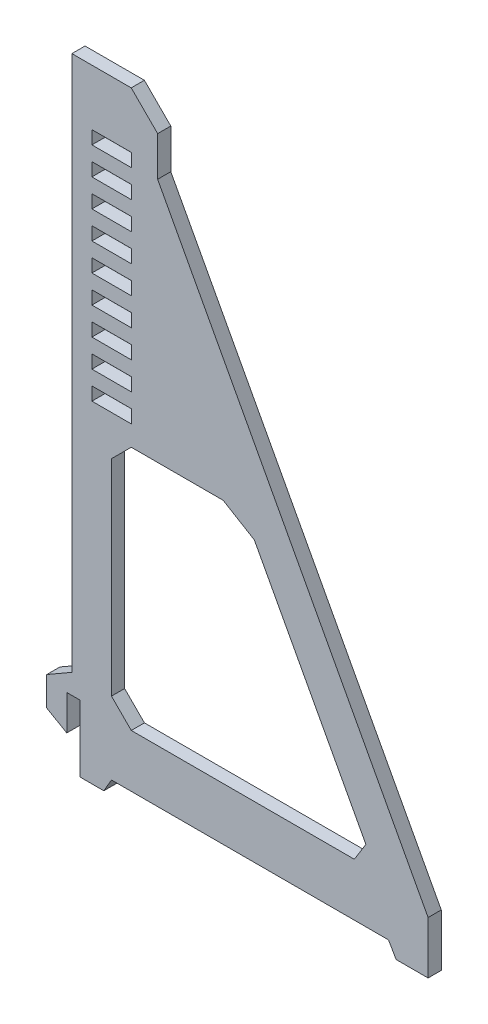
SolidWorks part; units mm, degrees
other "Markup1"
sketch "Sketch2" plane through (451.8627, 651.329, 334.843) normal (0.8622, 0.3297, 0.3847) x (0.4395, -0.109, -0.8916)
ref_plane "Front Plane" through (0, 0, 0) normal (0, 0, 1) x (1, 0, 0)
ref_plane "Top Plane" through (0, 0, 0) normal (0, 1, 0) x (1, 0, 0)
ref_plane "Right Plane" through (0, 0, 0) normal (1, 0, 0) x (0, 0, -1)
sketch "Sketch1" plane through (0, 0, 0) normal (0, 0, 1) x (1, 0, 0)
  line L1 (-15.6173, -25) -> (-13.1946, -25)
  line L2 (-15.6173, -25) -> (-15.6173, -22.8331)
  line L5 (-9.1173, 22.18) -> (-9.1173, 17.18)
  line L8 (-15.6173, 22.18) -> (-9.1173, 22.18)
  line L10 (-12.6173, -20) -> (7.4257, -20)
  line L11 (11.3827, -25) -> (11.3827, -21.0298)
  line L12 (-9.1173, 17.18) -> (11.3827, -21.0298)
  line L13 (-12.6173, -24) -> (8.3827, -24)
  line L14 (8.3827, -24) -> (8.9601, -25)
  line L15 (8.9601, -25) -> (9.8055, -25)
  line L16 (-12.6173, -1.41) -> (-2.548, -1.41) construction
  line L17 (-12.6173, -24) -> (-13.1946, -25)
  line L18 (8.9601, -25) -> (11.3827, -25)
  line L19 (-12.6173, -1.41) -> (-12.6173, -20)
  line L20 (-2.548, -1.41) -> (7.4257, -20)
  line L21 (-12.6173, -1.41) -> (-2.548, -1.41)
  line L22 (0.8565, -1.41) -> (27.1209, -1.41) construction
  line L23 (-15.6173, -18.4337) -> (-15.6173, 22.18)
  line L32 (-15.6173, -18.4337) -> (-17.5223, -19.5336)
  line L34 (-17.5223, -19.5336) -> (-17.5223, -21.7333)
  line L41 (-17.5223, -21.7333) -> (-15.6173, -22.8331)
  line L48 (-13.7123, -21.7333) -> (-13.7123, -19.5336) [skipped]
  line L49 (-14.6648, -18.9836) -> (-15.6173, -18.4337) [skipped]
  line L50 (-15.6173, -22.8331) -> (-14.6648, -22.2832) [skipped]
  point P0 (0, 0)
  dimension "D1" = 1
  dimension "D2" = 6.5
  dimension "D3" = 47.18
  dimension "D4" = 5
  dimension "D5" = 5
  dimension "D6" = 27
  dimension "D7" = 3
  dimension "D8" = 60
  dimension "D9" = 3
  dimension "D10" = 60
  dimension "D11" = 23.59
extrude "Boss-Extrude1" add sketch "Sketch1" along normal blind 25.4 contours L15 L18 L11 L12 L5 L8 L2 L1 L17 L13 L14 L19 L21 L20 L10
scale "Scale1" bodies to scale 101 scale about centroid uniform scaling yes scale factor 25.365591
sketch "Sketch3" plane through (0, 0, -309.443) normal (0, 0, -1) x (-1, 0, 0)
  line L1 (407.5134, -599.7995) -> (-634.8562, -599.7995)
  line L2 (407.5134, -599.7995) -> (407.5134, 673.4533)
  line L3 (407.5134, 673.4533) -> (-634.8562, 673.4533)
  line L4 (-634.8562, -599.7995) -> (-634.8562, 673.4533)
extrude "Cut-Extrude1" cut sketch "Sketch3" against normal blind 618.998
chamfer "Chamfer1" distance 50.8 angle 45 1 edges at (-65.0441, 656.7001, 322.199)
chamfer "Chamfer2" distance 38.1 angle 45 2 edges at (-153.8237, -413.2205, 322.199) (-153.8237, 58.3258, 322.199)
chamfer "Chamfer3" distance 40.64 angle 31 1 edges at (101.5889, 58.3258, 322.199)
chamfer "Chamfer4" distance 40.64 angle 60 1 edges at (354.5791, -413.2205, 322.199)
sketch "Sketch4" plane through (0, 0, 334.843) normal (0, 0, 1) x (1, 0, 0)
  line L0 (-229.9204, -540.0485) -> (-168.4685, -540.0485) construction
  line L1 (-214.3773, -540.0485) -> (-239.7773, -540.0485)
  line L2 (-214.3773, -540.0485) -> (-214.3773, -433.1771)
  line L3 (-214.3773, -433.1771) -> (-239.7773, -433.1771)
  line L4 (-239.7773, -540.0485) -> (-239.7773, -433.1771)
  dimension "D1" = 25.4
extrude "Cut-Extrude2" cut sketch "Sketch4" against normal blind 618.998 contours L2 L1 L4 L3
sketch "Sketch5" plane through (0, 0, 334.843) normal (0, 0, 1) x (1, 0, 0)
  line L0 (-191.4229, -540.0485) -> (-191.4229, 97.2375)
  line L1 (-214.3773, -540.0485) -> (-168.4685, -540.0485) construction
  line L2 (-191.4229, 150.5775) -> (-191.4229, 175.9775)
  line L3 (-191.4229, 97.2375) -> (-115.2229, 97.2375)
  line L4 (-191.4229, 97.2375) -> (-191.4229, 122.6375)
  line L5 (-191.4229, 122.6375) -> (-115.2229, 122.6375)
  line L6 (-115.2229, 97.2375) -> (-115.2229, 122.6375)
  line L7 (-191.4229, 150.5775) -> (-115.2229, 150.5775)
  line L8 (-115.2229, 150.5775) -> (-115.2229, 175.9775)
  line L9 (-191.4229, 175.9775) -> (-115.2229, 175.9775)
  line L10 (-191.4229, 203.9175) -> (-191.4229, 229.3175)
  line L11 (-191.4229, 203.9175) -> (-115.2229, 203.9175)
  line L12 (-115.2229, 203.9175) -> (-115.2229, 229.3175)
  line L13 (-191.4229, 229.3175) -> (-115.2229, 229.3175)
  line L14 (-191.4229, 257.2575) -> (-191.4229, 282.6575)
  line L15 (-191.4229, 257.2575) -> (-115.2229, 257.2575)
  line L16 (-115.2229, 257.2575) -> (-115.2229, 282.6575)
  line L17 (-191.4229, 282.6575) -> (-115.2229, 282.6575)
  line L18 (-191.4229, 310.5975) -> (-191.4229, 335.9975)
  line L19 (-191.4229, 310.5975) -> (-115.2229, 310.5975)
  line L20 (-115.2229, 310.5975) -> (-115.2229, 335.9975)
  line L21 (-191.4229, 335.9975) -> (-115.2229, 335.9975)
  line L22 (-191.4229, 363.9375) -> (-191.4229, 389.3375)
  line L23 (-191.4229, 363.9375) -> (-115.2229, 363.9375)
  line L24 (-115.2229, 363.9375) -> (-115.2229, 389.3375)
  line L25 (-191.4229, 389.3375) -> (-115.2229, 389.3375)
  line L26 (-191.4229, 417.2775) -> (-191.4229, 442.6775)
  line L27 (-191.4229, 417.2775) -> (-115.2229, 417.2775)
  line L28 (-115.2229, 417.2775) -> (-115.2229, 442.6775)
  line L29 (-191.4229, 442.6775) -> (-115.2229, 442.6775)
  line L30 (-201.6214, 424.1602) -> (-201.6214, 449.5602)
  line L31 (-201.6214, 424.1602) -> (-125.4214, 424.1602)
  line L32 (-125.4214, 424.1602) -> (-125.4214, 449.5602)
  line L33 (-201.6214, 449.5602) -> (-125.4214, 449.5602)
  dimension "D1" = 637.286
  dimension "D2" = 76.2
  dimension "D3" = 25.4
  dimension "D5" = 25.4
  dimension "D4" = 7
extrude "Cut-Extrude3" cut sketch "Sketch5" against normal through all contours L21 L18 L19 L20 | L13 L10 L11 L12 | L29 L28 L27 L26 | L25 L24 L23 L22 | L17 L16 L15 L14 | L9 L8 L7 L2 | L4 L5 L6 L3
pattern_linear "LPattern4" count 2 spacing 106.68 along (0, 1, 0) of "Cut-Extrude3"
sketch "Sketch6" plane through (-214.3773, 0, 0) normal (-1, 0, 0) x (0, 0, 1)
  line L3 (334.843, -433.1771) -> (309.555, -433.1771)
  line L4 (309.555, -433.1771) -> (309.555, -540.0485) construction
  line L6 (309.555, -433.1771) -> (334.843, -411.958)
  line L7 (334.843, -401.3888) -> (334.843, -457.1856) construction
  line L8 (334.843, -411.958) -> (334.843, -433.1771)
extrude "Cut-Extrude4" cut sketch "Sketch6" along normal blind 25.4
